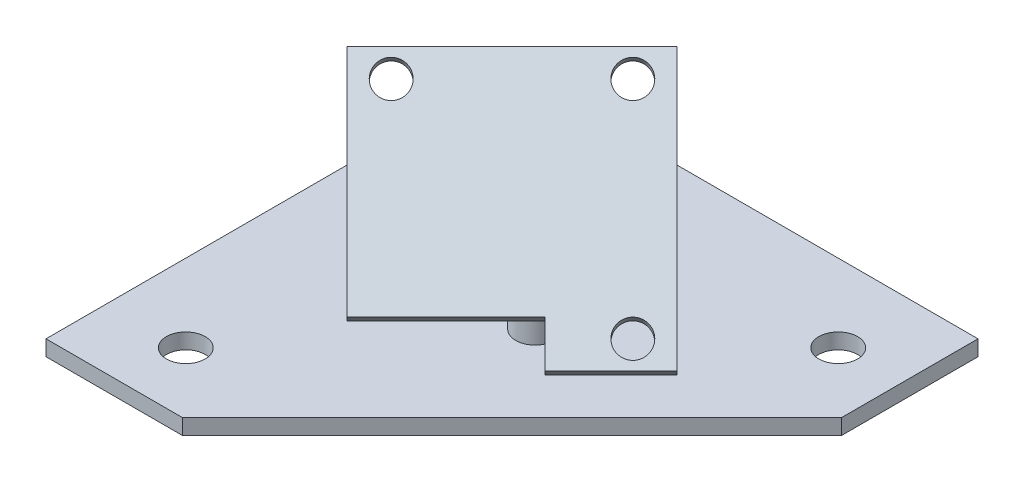
SolidWorks part; units mm, degrees
ref_plane "Front" through (0, 0, 0) normal (0, 0, 1) x (1, 0, 0)
ref_plane "Top" through (0, 0, 0) normal (0, 1, 0) x (1, 0, 0)
ref_plane "Right" through (0, 0, 0) normal (1, 0, 0) x (0, 0, -1)
sketch "草图1" plane through (0, 0, 0) normal (0, 1, 0) x (1, 0, 0)
  line L0 (90.71, 13.1364) -> (5.0331, -72.5405)
  line L1 (0, 0) -> (60, 0)
  line L2 (0, 0) -> (0, -60)
  line L3 (0, -60) -> (60, -60)
  line L4 (60, 0) -> (60, -60)
  line L5 (0, 0) -> (20, 0)
  line L6 (0, 0) -> (0, -20)
  line L7 (0, -20) -> (20, -20)
  line L8 (20, 0) -> (20, -20)
  circle A0 centre (10, -52) radius 2.5
  circle A1 centre (52, -10) radius 2.5
  dimension "D5" = 5
  dimension "D8" = 5
  dimension "D1" = 60
  dimension "D2" = 60
  dimension "D3" = 20
  dimension "D4" = 20
  dimension "D6" = 10
  dimension "D7" = 8
  dimension "D9" = 10
  dimension "D10" = 8
  dimension "D11" = 30
extrude "凸台-拉伸1" add sketch "草图1" along normal blind 2 contours L1 L8 L7 L2 L3 L4
ref_plane "基准面1" through (20.1005, 28.4264, 20.1005) normal (0.5, 0.7071, 0.5) x (-0.7071, 0, 0.7071)
sketch "草图2" plane through (20.1005, 28.4264, 20.1005) normal (0.5, 0.7071, 0.5) x (-0.7071, 0, 0.7071)
  line L0 (22.3297, 6.4312) -> (-19.7986, 6.4312) construction
  line L1 (-15, 33.4312) -> (15, 33.4312)
  line L2 (-15, 33.4312) -> (-15, 3.4312)
  line L3 (-15, 3.4312) -> (15, 3.4312)
  line L4 (15, 33.4312) -> (15, 3.4312)
  line L5 (-15, 33.4312) -> (15, 3.4312) construction
  line L6 (-15, 3.4312) -> (15, 33.4312) construction
  line L7 (0, -2.8326) -> (0, 36.0846) construction
  line L8 (29.0354, 18.4312) -> (-31.8996, 18.4312) construction
  line L10 (15, 33.4312) -> (-3, 33.4312)
  line L11 (15, 33.4312) -> (15, 28.4312)
  line L12 (15, 28.4312) -> (-3, 28.4312)
  line L13 (-3, 33.4312) -> (-3, 28.4312)
  circle A0 centre (11, 6.4312) radius 2
  circle A1 centre (-11, 6.4312) radius 2
  circle A2 centre (-11, 30.4312) radius 2
  circle A3 centre (11, 30.4312) radius 2
  point P0 (0, 18.4312)
  dimension "D4" = 4
  dimension "D1" = 30
  dimension "D2" = 30
  dimension "D3" = 12
  dimension "D5" = 11
  dimension "D6" = 5
  dimension "D7" = 18
extrude "凸台-拉伸3" add sketch "草图2" along normal blind 2 separate body contours L13 L1 L2 L3 L4 L12 A2 A0 A1
sketch "草图4" plane through (0, 2, 0) normal (0, 1, 0) x (1, 0, 0)
  line L12 (36.4374, -46.3369) -> (38.9374, -48.8369)
  line L13 (23.7095, -59.0649) -> (36.4374, -46.3369)
  line L14 (-2.9326, -32.4227) -> (23.7095, -59.0649)
  line L15 (32.4227, 2.9326) -> (-2.9326, -32.4227)
  line L16 (61.5649, -26.2095) -> (32.4227, 2.9326)
  line L17 (38.9374, -48.8369) -> (61.5649, -26.2095)
  line L18 (36.4374, -46.3369) -> (38.9374, -48.8369)
  line L19 (23.7095, -59.0649) -> (36.4374, -46.3369)
  line L20 (-2.9326, -32.4227) -> (23.7095, -59.0649)
  line L21 (32.4227, 2.9326) -> (-2.9326, -32.4227)
  line L22 (61.5649, -26.2095) -> (32.4227, 2.9326)
  line L23 (38.9374, -48.8369) -> (61.5649, -26.2095)
  circle A0 centre (30.4269, -27.4459) radius 2.5
  dimension "D2" = 5
  dimension "D1" = 10
extrude "凸台-拉伸4" add sketch "草图4" along normal up to surface (12.1628 mm away) contours A0
